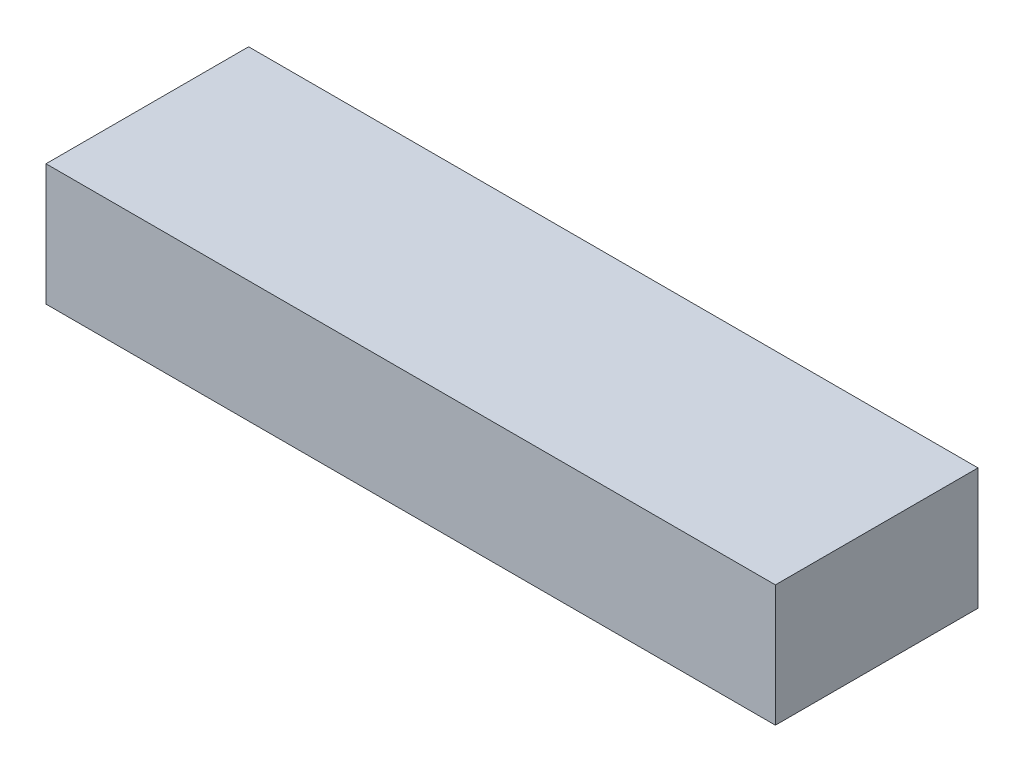
SolidWorks part; units mm, degrees
ref_plane "Front Plane" through (0, 0, 0) normal (0, 0, 1) x (1, 0, 0)
ref_plane "Top Plane" through (0, 0, 0) normal (0, 1, 0) x (1, 0, 0)
ref_plane "Right Plane" through (0, 0, 0) normal (1, 0, 0) x (0, 0, -1)
sketch "Sketch1" plane through (0, 0, 0) normal (0, 1, 0) x (1, 0, 0)
  line L1 (90, -25) -> (-90, -25)
  line L2 (90, -25) -> (90, 25)
  line L3 (90, 25) -> (-90, 25)
  line L4 (-90, -25) -> (-90, 25)
  line L5 (90, -25) -> (-90, 25) construction
  line L6 (90, 25) -> (-90, -25) construction
  point P0 (0, 0)
  dimension "D1" = 50
  dimension "D2" = 180
extrude "Boss-Extrude1" add sketch "Sketch1" along normal blind 30
